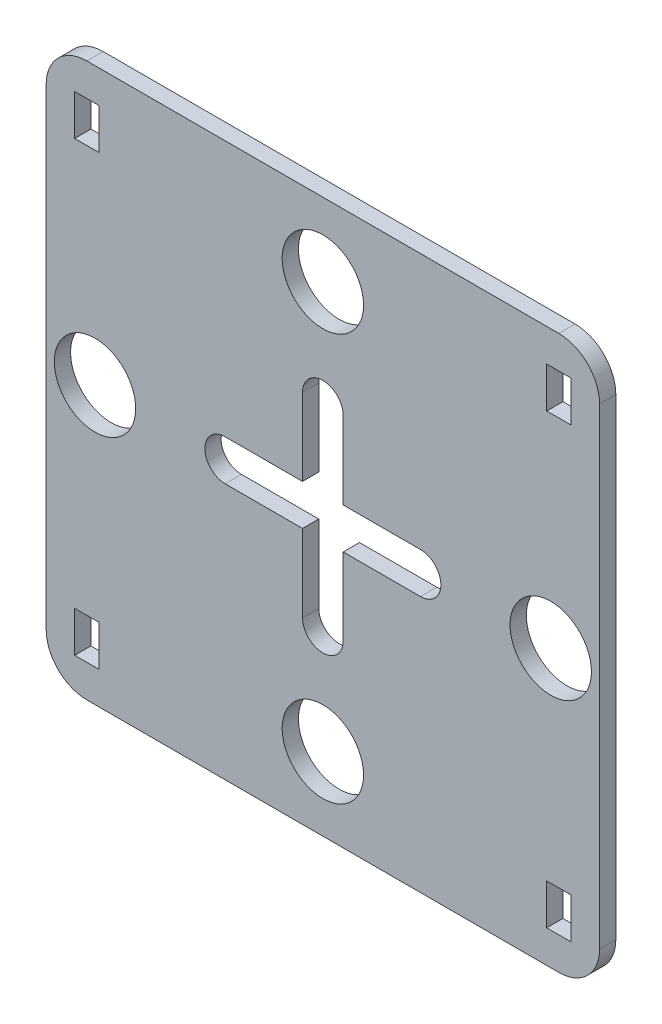
SolidWorks part; units mm, degrees
material "Thornel Mat VMA"
ref_plane "Ön Düzlem" through (0, 0, 0) normal (0, 0, 1) x (1, 0, 0)
ref_plane "Üst Düzlem" through (0, 0, 0) normal (0, 1, 0) x (1, 0, 0)
ref_plane "Sağ Düzlem" through (0, 0, 0) normal (1, 0, 0) x (0, 0, -1)
sketch "Sketch1" plane through (0, 0, 0) normal (0, 0, 1) x (1, 0, 0)
  line L0 (-28, 25) -> (28, 25) construction
  line L1 (30, 30) -> (28, 30)
  line L2 (30, 30) -> (30, 25)
  line L3 (-30, -30) -> (30, -30) construction
  line L4 (-30, -30) -> (-30, 30) construction
  line L5 (-30, 30) -> (30, 30) construction
  line L6 (30, -30) -> (30, 30) construction
  line L7 (-34, 34) -> (34, 34)
  line L8 (-34, 34) -> (-34, -34)
  line L9 (-34, -34) -> (34, -34)
  line L10 (34, 34) -> (34, -34)
  line L11 (30, 25) -> (28, 25)
  line L12 (28, 30) -> (28, 25)
  line L13 (30, -30) -> (28, -30)
  line L14 (30, -30) -> (30, -25)
  line L15 (30, -25) -> (28, -25)
  line L16 (28, -30) -> (28, -25)
  line L17 (-30, -30) -> (-28, -30)
  line L18 (-30, -30) -> (-30, -25)
  line L19 (-30, -25) -> (-28, -25)
  line L20 (-28, -30) -> (-28, -25)
  line L21 (-30, 30) -> (-28, 30)
  line L22 (-30, 30) -> (-30, 25)
  line L23 (-30, 25) -> (-28, 25)
  line L24 (-28, 30) -> (-28, 25)
  line L25 (28, 25) -> (28, -25) construction
  line L26 (-28, -25) -> (-28, 25) construction
  line L27 (-28, -25) -> (28, -25) construction
  line L28 (-12, 0) -> (12, 0) construction
  line L29 (-12, 2.5) -> (12, 2.5)
  line L30 (-12, -2.5) -> (12, -2.5)
  line L31 (0, 12) -> (0, -12) construction
  line L32 (2.5, 12) -> (2.5, -12)
  line L33 (-2.5, 12) -> (-2.5, -12)
  circle A0 centre (0, 25) radius 5
  circle A1 centre (28, 0) radius 5
  circle A2 centre (0, -25) radius 5
  circle A3 centre (-28, 0) radius 5
  arc A4 (-12, 2.5) -> (-12, -2.5) centre (-12, 0) ccw
  arc A5 (12, -2.5) -> (12, 2.5) centre (12, 0) ccw
  arc A6 (2.5, 12) -> (-2.5, 12) centre (0, 12) ccw
  arc A7 (-2.5, -12) -> (2.5, -12) centre (0, -12) ccw
  point P30 (0, 0)
  point P38 (0, 0)
  dimension "D13" = 16
  dimension "D1" = 2
  dimension "D2" = 4
  dimension "D3" = 4
  dimension "D4" = 4
  dimension "D5" = 4
  dimension "D6" = 5
  dimension "D7" = 2
  dimension "D8" = 5
  dimension "D9" = 2
  dimension "D10" = 5
  dimension "D11" = 2
  dimension "D12" = 5
  dimension "D14" = 16
  dimension "D15" = 5
  dimension "D16" = 24
  dimension "D17" = 5
extrude "Boss-Extrude1" add sketch "Sketch1" along normal blind 2 contours L10 L7 L8 L9 A7 L33 L30 A4 L29 A6 L32 A5 A3 A2 A1 A0 L13 L16 L15 L14 L12 L1 L2 L11 L20 L17 L18 L19 L21 L24 L23 L22
fillet "Fillet2" radius 5 1 edges at (34, 34, 1)
fillet "Fillet3" radius 5 1 edges at (-34, 34, 1)
fillet "Fillet4" radius 5 1 edges at (-34, -34, 1)
fillet "Fillet5" radius 5 1 edges at (34, -34, 1)
sketch "Sketch2" plane through (0, 0, 2) normal (0, 0, 1) x (1, 0, 0)
  line L0 (30, 25) -> (28, 25) construction
  line L1 (27.5, 25) -> (30.5, 25)
  line L2 (27.5, 25) -> (27.5, 30)
  line L3 (27.5, 30) -> (30.5, 30)
  line L4 (30.5, 25) -> (30.5, 30)
  line L5 (30, 30) -> (28, 30) construction
  line L6 (30, 30) -> (30, 25) construction
  line L7 (-30, 30) -> (-28, 30) construction
  line L8 (-30.5, 30) -> (-27.5, 30)
  line L9 (-30.5, 30) -> (-30.5, 25)
  line L10 (-30.5, 25) -> (-27.5, 25)
  line L11 (-27.5, 30) -> (-27.5, 25)
  line L12 (-30, 25) -> (-28, 25) construction
  line L13 (-28, 30) -> (-28, 25) construction
  line L14 (30, -25) -> (28, -25) construction
  line L15 (27.5, -25) -> (30.5, -25)
  line L16 (27.5, -25) -> (27.5, -30)
  line L17 (27.5, -30) -> (30.5, -30)
  line L18 (30.5, -25) -> (30.5, -30)
  line L19 (30, -30) -> (28, -30) construction
  line L20 (30, -30) -> (30, -25) construction
  line L21 (-30, -25) -> (-28, -25) construction
  line L22 (-30.5, -25) -> (-27.5, -25)
  line L23 (-30.5, -25) -> (-30.5, -30)
  line L24 (-30.5, -30) -> (-27.5, -30)
  line L25 (-27.5, -25) -> (-27.5, -30)
  line L26 (-30, -30) -> (-28, -30) construction
  line L27 (-28, -30) -> (-28, -25) construction
  dimension "D1" = 3
  dimension "D2" = 0.5
  dimension "D3" = 3
  dimension "D4" = 0.5
  dimension "D5" = 3
  dimension "D6" = 0.5
  dimension "D7" = 3
  dimension "D8" = 0.5
extrude "Cut-Extrude1" cut sketch "Sketch2" against normal blind 10
